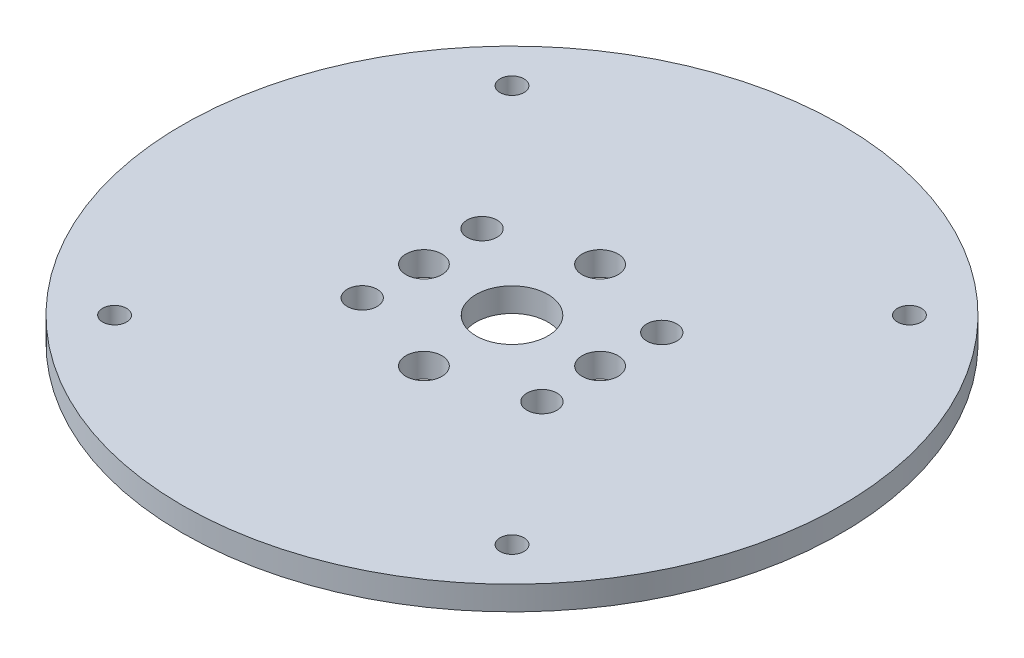
SolidWorks part; units mm, degrees
ref_plane "Alzado" through (0, 0, 0) normal (0, 0, 1) x (1, 0, 0)
ref_plane "Planta" through (0, 0, 0) normal (0, 1, 0) x (1, 0, 0)
ref_plane "Vista lateral" through (0, 0, 0) normal (1, 0, 0) x (0, 0, -1)
sketch "Croquis base" plane through (0, 0, 0) normal (0, 1, 0) x (1, 0, 0)
  line L0 (-26.3516, 1.0929) -> (28.6484, 1.0929) construction
  line L1 (1.1484, 28.5929) -> (1.1484, -26.4071) construction
  line L2 (-6.3516, -3.9071) -> (8.6484, -3.9071) construction
  line L3 (-6.3516, -3.9071) -> (-6.3516, 6.0929) construction
  line L4 (-6.3516, 6.0929) -> (8.6484, 6.0929) construction
  line L5 (8.6484, -3.9071) -> (8.6484, 6.0929) construction
  line L6 (-6.3516, -3.9071) -> (8.6484, 6.0929) construction
  line L7 (-6.3516, 6.0929) -> (8.6484, -3.9071) construction
  line L8 (-15.4331, -15.4886) -> (17.7299, -15.4886) construction
  line L9 (-15.4331, -15.4886) -> (-15.4331, 17.6744) construction
  line L10 (-15.4331, 17.6744) -> (17.7299, 17.6744) construction
  line L11 (17.7299, -15.4886) -> (17.7299, 17.6744) construction
  line L12 (-15.4331, -15.4886) -> (17.7299, 17.6744) construction
  line L13 (-15.4331, 17.6744) -> (17.7299, -15.4886) construction
  circle A0 centre (1.1484, 1.0929) radius 27.5
  circle A1 centre (1.1484, 1.0929) radius 3
  circle A2 centre (-6.2016, 1.0929) radius 1.5
  circle A3 centre (1.1484, 8.4429) radius 1.5
  circle A4 centre (8.4984, 1.0929) radius 1.5
  circle A5 centre (1.1484, -6.2571) radius 1.5
  circle A6 centre (-6.3516, 6.0929) radius 1.25
  circle A7 centre (8.6484, 6.0929) radius 1.25
  circle A8 centre (8.6484, -3.9071) radius 1.25
  circle A9 centre (-6.3516, -3.9071) radius 1.25
  circle A10 centre (-15.4331, 17.6744) radius 1
  circle A11 centre (17.7299, 17.6744) radius 1
  circle A12 centre (17.7299, -15.4886) radius 1
  circle A13 centre (-15.4331, -15.4886) radius 1
  dimension "D1" = 7.35
  dimension "D2" = 15
  dimension "D3" = 10
  dimension "D4" = 33.163
  dimension "D5" = 33.163
extrude "Saliente-Extruir1" add sketch "Croquis base" along normal blind 2
